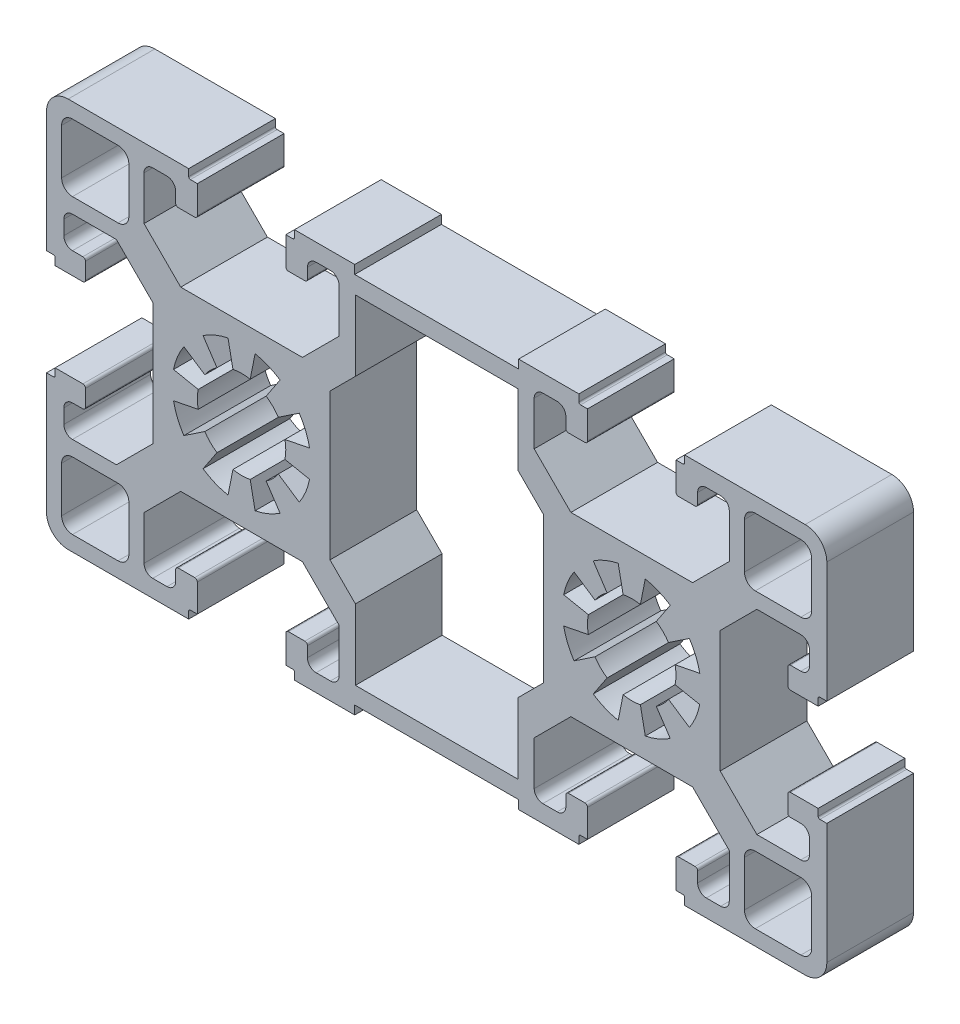
SolidWorks part; units mm, degrees
ref_plane "前视基准面" through (0, 0, 0) normal (0, 0, 1) x (1, 0, 0)
ref_plane "上视基准面" through (0, 0, 0) normal (0, 1, 0) x (1, 0, 0)
ref_plane "右视基准面" through (0, 0, 0) normal (1, 0, 0) x (0, 0, -1)
sketch "草图1" plane through (0, 0, 0) normal (0, 0, 1) x (1, 0, 0)
  line L0 (-64.3456, 3.0482) -> (-78.2456, 3.0482)
  line L1 (-80.7456, 0.5482) -> (-80.7456, -13.3518)
  line L2 (-63.3456, 2.0482) -> (-63.3456, -1.1518)
  line L3 (-63.6456, -1.4518) -> (-65.5456, -1.4518)
  line L4 (-65.8456, -1.1518) -> (-65.8456, 0.0482)
  line L5 (-66.8456, 1.0482) -> (-68.4956, 1.0482)
  line L6 (-69.4956, 0.0482) -> (-69.4956, -5.0198)
  line L7 (-77.7456, -6.4518) -> (-72.4956, -6.4518)
  line L8 (-71.2456, -5.2018) -> (-71.2456, 0.0482)
  line L9 (-72.4956, 1.2982) -> (-77.7456, 1.2982)
  line L10 (-78.9956, 0.0482) -> (-78.9956, -5.2018)
  line L11 (-72.6776, -8.2018) -> (-77.7456, -8.2018)
  line L12 (-78.7456, -9.2018) -> (-78.7456, -10.8518)
  line L13 (-77.7456, -11.8518) -> (-76.5456, -11.8518)
  line L14 (-76.2456, -12.1518) -> (-76.2456, -14.0518)
  line L15 (-76.5456, -14.3518) -> (-79.7456, -14.3518)
  line L16 (-63.3456, 2.0482) -> (-64.1456, 2.0482)
  line L17 (-64.3456, 2.2482) -> (-64.3456, 3.0482)
  line L18 (-80.7456, -13.3518) -> (-79.9456, -13.3518)
  line L19 (-79.7456, -13.5518) -> (-79.7456, -14.3518)
  line L20 (-53.1456, 2.0482) -> (-53.1456, -1.1518)
  line L21 (-52.8456, -1.4518) -> (-50.9456, -1.4518)
  line L22 (-50.6456, -1.1518) -> (-50.6456, 0.0482)
  line L23 (-49.6456, 1.0482) -> (-47.9956, 1.0482)
  line L24 (-46.9956, 0.0482) -> (-46.9956, -5.0198)
  line L25 (-53.1456, 2.0482) -> (-52.3456, 2.0482)
  line L26 (-52.1456, 2.2482) -> (-52.1456, 3.0482)
  line L27 (-64.3456, -41.9518) -> (-78.2456, -41.9518)
  line L28 (-80.7456, -39.4518) -> (-80.7456, -25.5518)
  line L29 (-63.3456, -40.9518) -> (-63.3456, -37.7518)
  line L30 (-63.6456, -37.4518) -> (-65.5456, -37.4518)
  line L31 (-65.8456, -37.7518) -> (-65.8456, -38.9518)
  line L32 (-66.8456, -39.9518) -> (-68.4956, -39.9518)
  line L33 (-69.4956, -38.9518) -> (-69.4956, -33.8838)
  line L34 (-77.7456, -32.4518) -> (-72.4956, -32.4518)
  line L35 (-71.2456, -33.7018) -> (-71.2456, -38.9518)
  line L36 (-72.4956, -40.2018) -> (-77.7456, -40.2018)
  line L37 (-78.9956, -38.9518) -> (-78.9956, -33.7018)
  line L38 (-72.6776, -30.7018) -> (-77.7456, -30.7018)
  line L39 (-78.7456, -29.7018) -> (-78.7456, -28.0518)
  line L40 (-77.7456, -27.0518) -> (-76.5456, -27.0518)
  line L41 (-76.2456, -26.7518) -> (-76.2456, -24.8518)
  line L42 (-76.5456, -24.5518) -> (-79.7456, -24.5518)
  line L43 (-63.3456, -40.9518) -> (-64.1456, -40.9518)
  line L44 (-64.3456, -41.1518) -> (-64.3456, -41.9518)
  line L45 (-80.7456, -25.5518) -> (-79.9456, -25.5518)
  line L46 (-79.7456, -25.3518) -> (-79.7456, -24.5518)
  line L47 (-53.1456, -40.9518) -> (-53.1456, -37.7518)
  line L48 (-52.8456, -37.4518) -> (-50.9456, -37.4518)
  line L49 (-50.6456, -37.7518) -> (-50.6456, -38.9518)
  line L50 (-49.6456, -39.9518) -> (-47.9956, -39.9518)
  line L51 (-46.9956, -38.9518) -> (-46.9956, -33.8838)
  line L52 (-53.1456, -40.9518) -> (-52.3456, -40.9518)
  line L53 (-52.1456, -41.1518) -> (-52.1456, -41.9518)
  line L54 (-62.6902, -26.1035) -> (-61.079, -23.6923)
  line L55 (-59.8063, -27.2981) -> (-59.2406, -24.4538)
  line L56 (-56.6849, -27.2981) -> (-57.2507, -24.4538)
  line L57 (-53.8011, -26.1035) -> (-55.4122, -23.6923)
  line L58 (-51.5939, -23.8964) -> (-54.0051, -22.2852)
  line L59 (-50.3993, -21.0125) -> (-53.2436, -20.4467)
  line L60 (-50.3993, -17.8911) -> (-53.2436, -18.4568)
  line L61 (-51.5939, -15.0072) -> (-54.0051, -16.6184)
  line L62 (-53.8011, -12.8) -> (-55.4122, -15.2113)
  line L63 (-56.6849, -11.6055) -> (-57.2507, -14.4498)
  line L64 (-59.8063, -11.6055) -> (-59.2406, -14.4498)
  line L65 (-62.6902, -12.8) -> (-61.079, -15.2113)
  line L66 (-64.8974, -15.0072) -> (-62.4861, -16.6184)
  line L67 (-66.0919, -17.8911) -> (-63.2476, -18.4568)
  line L68 (-66.0919, -21.0125) -> (-63.2476, -20.4467)
  line L69 (-64.8974, -23.8964) -> (-62.4861, -22.2852)
  line L71 (-51.2276, -9.2518) -> (-65.2636, -9.2518)
  line L72 (-68.4456, -12.4338) -> (-68.4456, -26.4698)
  line L73 (-65.2636, -29.6518) -> (-51.2276, -29.6518)
  line L74 (-69.4956, -5.0198) -> (-65.2636, -9.2518)
  line L75 (-72.6776, -8.2018) -> (-68.4456, -12.4338)
  line L76 (-46.9956, -5.0198) -> (-51.2276, -9.2518)
  line L77 (-69.4956, -33.8838) -> (-65.2636, -29.6518)
  line L78 (-72.6776, -30.7018) -> (-68.4456, -26.4698)
  line L79 (-46.9956, -33.8838) -> (-51.2276, -29.6518)
  line L80 (-18.3456, 2.0482) -> (-18.3456, -1.1518)
  line L81 (-18.6456, -1.4518) -> (-20.5456, -1.4518)
  line L82 (-20.8456, -1.1518) -> (-20.8456, 0.0482)
  line L83 (-21.8456, 1.0482) -> (-23.4956, 1.0482)
  line L84 (-24.4956, 0.0482) -> (-24.4956, -5.0198)
  line L85 (-18.3456, 2.0482) -> (-19.1456, 2.0482)
  line L86 (-19.3456, 2.2482) -> (-19.3456, 3.0482)
  line L87 (-7.1456, 3.0482) -> (6.7544, 3.0482)
  line L88 (9.2544, 0.5482) -> (9.2544, -13.3518)
  line L89 (-8.1456, 2.0482) -> (-8.1456, -1.1518)
  line L90 (-7.8456, -1.4518) -> (-5.9456, -1.4518)
  line L91 (-5.6456, -1.1518) -> (-5.6456, 0.0482)
  line L92 (-4.6456, 1.0482) -> (-2.9956, 1.0482)
  line L93 (-1.9956, 0.0482) -> (-1.9956, -5.0198)
  line L94 (6.2544, -6.4518) -> (1.0044, -6.4518)
  line L95 (-0.2456, -5.2018) -> (-0.2456, 0.0482)
  line L96 (1.0044, 1.2982) -> (6.2544, 1.2982)
  line L97 (7.5044, 0.0482) -> (7.5044, -5.2018)
  line L98 (1.1864, -8.2018) -> (6.2544, -8.2018)
  line L99 (7.2544, -9.2018) -> (7.2544, -10.8518)
  line L100 (6.2544, -11.8518) -> (5.0544, -11.8518)
  line L101 (4.7544, -12.1518) -> (4.7544, -14.0518)
  line L102 (5.0544, -14.3518) -> (8.2544, -14.3518)
  line L103 (-8.1456, 2.0482) -> (-7.3456, 2.0482)
  line L104 (-7.1456, 2.2482) -> (-7.1456, 3.0482)
  line L105 (9.2544, -13.3518) -> (8.4544, -13.3518)
  line L106 (8.2544, -13.5518) -> (8.2544, -14.3518)
  line L107 (-18.3456, -40.9518) -> (-18.3456, -37.7518)
  line L108 (-18.6456, -37.4518) -> (-20.5456, -37.4518)
  line L109 (-20.8456, -37.7518) -> (-20.8456, -38.9518)
  line L110 (-21.8456, -39.9518) -> (-23.4956, -39.9518)
  line L111 (-24.4956, -38.9518) -> (-24.4956, -33.8838)
  line L112 (-18.3456, -40.9518) -> (-19.1456, -40.9518)
  line L113 (-19.3456, -41.1518) -> (-19.3456, -41.9518)
  line L114 (-7.1456, -41.9518) -> (6.7544, -41.9518)
  line L115 (9.2544, -39.4518) -> (9.2544, -25.5518)
  line L116 (-8.1456, -40.9518) -> (-8.1456, -37.7518)
  line L117 (-7.8456, -37.4518) -> (-5.9456, -37.4518)
  line L118 (-5.6456, -37.7518) -> (-5.6456, -38.9518)
  line L119 (-4.6456, -39.9518) -> (-2.9956, -39.9518)
  line L120 (-1.9956, -38.9518) -> (-1.9956, -33.8838)
  line L121 (6.2544, -32.4518) -> (1.0044, -32.4518)
  line L122 (-0.2456, -33.7018) -> (-0.2456, -38.9518)
  line L123 (1.0044, -40.2018) -> (6.2544, -40.2018)
  line L124 (7.5044, -38.9518) -> (7.5044, -33.7018)
  line L125 (1.1864, -30.7018) -> (6.2544, -30.7018)
  line L126 (7.2544, -29.7018) -> (7.2544, -28.0518)
  line L127 (6.2544, -27.0518) -> (5.0544, -27.0518)
  line L128 (4.7544, -26.7518) -> (4.7544, -24.8518)
  line L129 (5.0544, -24.5518) -> (8.2544, -24.5518)
  line L130 (-8.1456, -40.9518) -> (-7.3456, -40.9518)
  line L131 (-7.1456, -41.1518) -> (-7.1456, -41.9518)
  line L132 (9.2544, -25.5518) -> (8.4544, -25.5518)
  line L133 (8.2544, -25.3518) -> (8.2544, -24.5518)
  line L134 (-17.6902, -26.1035) -> (-16.079, -23.6923)
  line L135 (-14.8063, -27.2981) -> (-14.2406, -24.4538)
  line L136 (-11.6849, -27.2981) -> (-12.2507, -24.4538)
  line L137 (-8.8011, -26.1035) -> (-10.4122, -23.6923)
  line L138 (-6.5939, -23.8964) -> (-9.0051, -22.2852)
  line L139 (-5.3993, -21.0125) -> (-8.2436, -20.4467)
  line L140 (-5.3993, -17.8911) -> (-8.2436, -18.4568)
  line L141 (-6.5939, -15.0072) -> (-9.0051, -16.6184)
  line L142 (-8.8011, -12.8) -> (-10.4122, -15.2113)
  line L143 (-11.6849, -11.6055) -> (-12.2507, -14.4498)
  line L144 (-14.8063, -11.6055) -> (-14.2406, -14.4498)
  line L145 (-17.6902, -12.8) -> (-16.079, -15.2113)
  line L146 (-19.8974, -15.0072) -> (-17.4861, -16.6184)
  line L147 (-21.0919, -17.8911) -> (-18.2476, -18.4568)
  line L148 (-21.0919, -21.0125) -> (-18.2476, -20.4467)
  line L149 (-19.8974, -23.8964) -> (-17.4861, -22.2852)
  line L150 (-3.0456, -26.4698) -> (-3.0456, -12.4338)
  line L151 (-6.2276, -9.2518) -> (-20.2636, -9.2518)
  line L153 (-20.2636, -29.6518) -> (-6.2276, -29.6518)
  line L154 (-24.4956, -5.0198) -> (-20.2636, -9.2518)
  line L155 (-1.9956, -5.0198) -> (-6.2276, -9.2518)
  line L156 (1.1864, -8.2018) -> (-3.0456, -12.4338)
  line L157 (-24.4956, -33.8838) -> (-20.2636, -29.6518)
  line L158 (-1.9956, -33.8838) -> (-6.2276, -29.6518)
  line L159 (1.1864, -30.7018) -> (-3.0456, -26.4698)
  line L160 (-52.1456, 3.0482) -> (-45.1956, 3.0482)
  line L161 (-45.1956, 2.0482) -> (-26.2956, 2.0482)
  line L162 (-45.1163, 0.0482) -> (-26.375, 0.0482)
  line L163 (-45.1163, -8.0902) -> (-48.0456, -11.0196)
  line L164 (-45.1163, -30.8134) -> (-48.0456, -27.884)
  line L165 (-19.3456, 3.0482) -> (-26.2956, 3.0482)
  line L166 (-26.375, -8.0902) -> (-23.4456, -11.0196)
  line L167 (-26.375, -30.8134) -> (-23.4456, -27.884)
  line L168 (-52.1456, -41.9518) -> (-45.1956, -41.9518)
  line L169 (-26.2956, -41.9518) -> (-19.3456, -41.9518)
  line L170 (-45.1956, -40.9518) -> (-26.2956, -40.9518)
  line L171 (-26.2956, -41.9518) -> (-26.2956, -40.9518)
  line L172 (-26.2956, 2.0482) -> (-26.2956, 3.0482)
  line L173 (-45.1956, -41.9518) -> (-45.1956, -40.9518)
  line L174 (-45.1956, 2.0482) -> (-45.1956, 3.0482)
  line L175 (-48.0456, -11.0196) -> (-48.0456, -27.884)
  line L176 (-23.4456, -11.0196) -> (-23.4456, -27.884)
  line L177 (-45.1163, -8.0902) -> (-45.1163, 0.0482)
  line L178 (-26.375, -8.0902) -> (-26.375, 0.0482)
  line L179 (-45.1163, -38.9518) -> (-26.375, -38.9518)
  line L180 (-45.1163, -30.8134) -> (-45.1163, -38.9518)
  line L181 (-26.375, -30.8134) -> (-26.375, -38.9518)
  arc A0 (-78.2456, 3.0482) -> (-80.7456, 0.5482) centre (-78.2456, 0.5482) ccw
  arc A1 (-63.6456, -1.4518) -> (-63.3456, -1.1518) centre (-63.6456, -1.1518) ccw
  arc A2 (-65.8456, -1.1518) -> (-65.5456, -1.4518) centre (-65.5456, -1.1518) ccw
  arc A3 (-65.8456, 0.0482) -> (-66.8456, 1.0482) centre (-66.8456, 0.0482) ccw
  arc A4 (-68.4956, 1.0482) -> (-69.4956, 0.0482) centre (-68.4956, 0.0482) ccw
  arc A5 (-72.4956, -6.4518) -> (-71.2456, -5.2018) centre (-72.4956, -5.2018) ccw
  arc A6 (-71.2456, 0.0482) -> (-72.4956, 1.2982) centre (-72.4956, 0.0482) ccw
  arc A7 (-77.7456, 1.2982) -> (-78.9956, 0.0482) centre (-77.7456, 0.0482) ccw
  arc A8 (-78.9956, -5.2018) -> (-77.7456, -6.4518) centre (-77.7456, -5.2018) ccw
  arc A9 (-77.7456, -8.2018) -> (-78.7456, -9.2018) centre (-77.7456, -9.2018) ccw
  arc A10 (-78.7456, -10.8518) -> (-77.7456, -11.8518) centre (-77.7456, -10.8518) ccw
  arc A11 (-76.2456, -12.1518) -> (-76.5456, -11.8518) centre (-76.5456, -12.1518) ccw
  arc A12 (-76.5456, -14.3518) -> (-76.2456, -14.0518) centre (-76.5456, -14.0518) ccw
  arc A13 (-64.3456, 2.2482) -> (-64.1456, 2.0482) centre (-64.1456, 2.2482) ccw
  arc A14 (-79.7456, -13.5518) -> (-79.9456, -13.3518) centre (-79.9456, -13.5518) ccw
  arc A15 (-59.2406, -24.4538) -> (-57.2507, -24.4538) centre (-58.2456, -19.4518) ccw
  arc A16 (-55.4122, -23.6923) -> (-54.0051, -22.2852) centre (-58.2456, -19.4518) ccw
  arc A17 (-53.2436, -20.4467) -> (-53.2436, -18.4568) centre (-58.2456, -19.4518) ccw
  arc A18 (-54.0051, -16.6184) -> (-55.4122, -15.2113) centre (-58.2456, -19.4518) ccw
  arc A19 (-57.2507, -14.4498) -> (-59.2406, -14.4498) centre (-58.2456, -19.4518) ccw
  arc A20 (-61.079, -15.2113) -> (-62.4861, -16.6184) centre (-58.2456, -19.4518) ccw
  arc A21 (-63.2476, -18.4568) -> (-63.2476, -20.4467) centre (-58.2456, -19.4518) ccw
  arc A22 (-62.4861, -22.2852) -> (-61.079, -23.6923) centre (-58.2456, -19.4518) ccw
  arc A23 (-62.6902, -26.1035) -> (-59.8063, -27.2981) centre (-58.2456, -19.4518) ccw
  arc A24 (-56.6849, -27.2981) -> (-53.8011, -26.1035) centre (-58.2456, -19.4518) ccw
  arc A25 (-51.5939, -23.8964) -> (-50.3993, -21.0125) centre (-58.2456, -19.4518) ccw
  arc A26 (-50.3993, -17.8911) -> (-51.5939, -15.0072) centre (-58.2456, -19.4518) ccw
  arc A27 (-53.8011, -12.8) -> (-56.6849, -11.6055) centre (-58.2456, -19.4518) ccw
  arc A28 (-59.8063, -11.6055) -> (-62.6902, -12.8) centre (-58.2456, -19.4518) ccw
  arc A29 (-64.8974, -15.0072) -> (-66.0919, -17.8911) centre (-58.2456, -19.4518) ccw
  arc A30 (-66.0919, -21.0125) -> (-64.8974, -23.8964) centre (-58.2456, -19.4518) ccw
  arc A31 (-53.1456, -1.1518) -> (-52.8456, -1.4518) centre (-52.8456, -1.1518) ccw
  arc A32 (-50.9456, -1.4518) -> (-50.6456, -1.1518) centre (-50.9456, -1.1518) ccw
  arc A33 (-49.6456, 1.0482) -> (-50.6456, 0.0482) centre (-49.6456, 0.0482) ccw
  arc A34 (-46.9956, 0.0482) -> (-47.9956, 1.0482) centre (-47.9956, 0.0482) ccw
  arc A35 (-52.3456, 2.0482) -> (-52.1456, 2.2482) centre (-52.3456, 2.2482) ccw
  arc A36 (-80.7456, -39.4518) -> (-78.2456, -41.9518) centre (-78.2456, -39.4518) ccw
  arc A37 (-63.3456, -37.7518) -> (-63.6456, -37.4518) centre (-63.6456, -37.7518) ccw
  arc A38 (-65.5456, -37.4518) -> (-65.8456, -37.7518) centre (-65.5456, -37.7518) ccw
  arc A39 (-66.8456, -39.9518) -> (-65.8456, -38.9518) centre (-66.8456, -38.9518) ccw
  arc A40 (-69.4956, -38.9518) -> (-68.4956, -39.9518) centre (-68.4956, -38.9518) ccw
  arc A41 (-71.2456, -33.7018) -> (-72.4956, -32.4518) centre (-72.4956, -33.7018) ccw
  arc A42 (-72.4956, -40.2018) -> (-71.2456, -38.9518) centre (-72.4956, -38.9518) ccw
  arc A43 (-78.9956, -38.9518) -> (-77.7456, -40.2018) centre (-77.7456, -38.9518) ccw
  arc A44 (-77.7456, -32.4518) -> (-78.9956, -33.7018) centre (-77.7456, -33.7018) ccw
  arc A45 (-78.7456, -29.7018) -> (-77.7456, -30.7018) centre (-77.7456, -29.7018) ccw
  arc A46 (-77.7456, -27.0518) -> (-78.7456, -28.0518) centre (-77.7456, -28.0518) ccw
  arc A47 (-76.5456, -27.0518) -> (-76.2456, -26.7518) centre (-76.5456, -26.7518) ccw
  arc A48 (-76.2456, -24.8518) -> (-76.5456, -24.5518) centre (-76.5456, -24.8518) ccw
  arc A49 (-64.1456, -40.9518) -> (-64.3456, -41.1518) centre (-64.1456, -41.1518) ccw
  arc A50 (-79.9456, -25.5518) -> (-79.7456, -25.3518) centre (-79.9456, -25.3518) ccw
  arc A51 (-52.8456, -37.4518) -> (-53.1456, -37.7518) centre (-52.8456, -37.7518) ccw
  arc A52 (-50.6456, -37.7518) -> (-50.9456, -37.4518) centre (-50.9456, -37.7518) ccw
  arc A53 (-50.6456, -38.9518) -> (-49.6456, -39.9518) centre (-49.6456, -38.9518) ccw
  arc A54 (-47.9956, -39.9518) -> (-46.9956, -38.9518) centre (-47.9956, -38.9518) ccw
  arc A55 (-52.1456, -41.1518) -> (-52.3456, -40.9518) centre (-52.3456, -41.1518) ccw
  arc A56 (-18.6456, -1.4518) -> (-18.3456, -1.1518) centre (-18.6456, -1.1518) ccw
  arc A57 (-20.8456, -1.1518) -> (-20.5456, -1.4518) centre (-20.5456, -1.1518) ccw
  arc A58 (-20.8456, 0.0482) -> (-21.8456, 1.0482) centre (-21.8456, 0.0482) ccw
  arc A59 (-23.4956, 1.0482) -> (-24.4956, 0.0482) centre (-23.4956, 0.0482) ccw
  arc A60 (-19.3456, 2.2482) -> (-19.1456, 2.0482) centre (-19.1456, 2.2482) ccw
  arc A61 (-14.2406, -24.4538) -> (-12.2507, -24.4538) centre (-13.2456, -19.4518) ccw
  arc A62 (-10.4122, -23.6923) -> (-9.0051, -22.2852) centre (-13.2456, -19.4518) ccw
  arc A63 (-8.2436, -20.4467) -> (-8.2436, -18.4568) centre (-13.2456, -19.4518) ccw
  arc A64 (-9.0051, -16.6184) -> (-10.4122, -15.2113) centre (-13.2456, -19.4518) ccw
  arc A65 (-12.2507, -14.4498) -> (-14.2406, -14.4498) centre (-13.2456, -19.4518) ccw
  arc A66 (-16.079, -15.2113) -> (-17.4861, -16.6184) centre (-13.2456, -19.4518) ccw
  arc A67 (-18.2476, -18.4568) -> (-18.2476, -20.4467) centre (-13.2456, -19.4518) ccw
  arc A68 (-17.4861, -22.2852) -> (-16.079, -23.6923) centre (-13.2456, -19.4518) ccw
  arc A69 (-17.6902, -26.1035) -> (-14.8063, -27.2981) centre (-13.2456, -19.4518) ccw
  arc A70 (-11.6849, -27.2981) -> (-8.8011, -26.1035) centre (-13.2456, -19.4518) ccw
  arc A71 (-6.5939, -23.8964) -> (-5.3993, -21.0125) centre (-13.2456, -19.4518) ccw
  arc A72 (-5.3993, -17.8911) -> (-6.5939, -15.0072) centre (-13.2456, -19.4518) ccw
  arc A73 (-8.8011, -12.8) -> (-11.6849, -11.6055) centre (-13.2456, -19.4518) ccw
  arc A74 (-14.8063, -11.6055) -> (-17.6902, -12.8) centre (-13.2456, -19.4518) ccw
  arc A75 (-19.8974, -15.0072) -> (-21.0919, -17.8911) centre (-13.2456, -19.4518) ccw
  arc A76 (-21.0919, -21.0125) -> (-19.8974, -23.8964) centre (-13.2456, -19.4518) ccw
  arc A77 (9.2544, 0.5482) -> (6.7544, 3.0482) centre (6.7544, 0.5482) ccw
  arc A78 (-8.1456, -1.1518) -> (-7.8456, -1.4518) centre (-7.8456, -1.1518) ccw
  arc A79 (-5.9456, -1.4518) -> (-5.6456, -1.1518) centre (-5.9456, -1.1518) ccw
  arc A80 (-4.6456, 1.0482) -> (-5.6456, 0.0482) centre (-4.6456, 0.0482) ccw
  arc A81 (-1.9956, 0.0482) -> (-2.9956, 1.0482) centre (-2.9956, 0.0482) ccw
  arc A82 (-0.2456, -5.2018) -> (1.0044, -6.4518) centre (1.0044, -5.2018) ccw
  arc A83 (1.0044, 1.2982) -> (-0.2456, 0.0482) centre (1.0044, 0.0482) ccw
  arc A84 (7.5044, 0.0482) -> (6.2544, 1.2982) centre (6.2544, 0.0482) ccw
  arc A85 (6.2544, -6.4518) -> (7.5044, -5.2018) centre (6.2544, -5.2018) ccw
  arc A86 (7.2544, -9.2018) -> (6.2544, -8.2018) centre (6.2544, -9.2018) ccw
  arc A87 (6.2544, -11.8518) -> (7.2544, -10.8518) centre (6.2544, -10.8518) ccw
  arc A88 (5.0544, -11.8518) -> (4.7544, -12.1518) centre (5.0544, -12.1518) ccw
  arc A89 (4.7544, -14.0518) -> (5.0544, -14.3518) centre (5.0544, -14.0518) ccw
  arc A90 (-7.3456, 2.0482) -> (-7.1456, 2.2482) centre (-7.3456, 2.2482) ccw
  arc A91 (8.4544, -13.3518) -> (8.2544, -13.5518) centre (8.4544, -13.5518) ccw
  arc A92 (-18.3456, -37.7518) -> (-18.6456, -37.4518) centre (-18.6456, -37.7518) ccw
  arc A93 (-20.5456, -37.4518) -> (-20.8456, -37.7518) centre (-20.5456, -37.7518) ccw
  arc A94 (-21.8456, -39.9518) -> (-20.8456, -38.9518) centre (-21.8456, -38.9518) ccw
  arc A95 (-24.4956, -38.9518) -> (-23.4956, -39.9518) centre (-23.4956, -38.9518) ccw
  arc A96 (-19.1456, -40.9518) -> (-19.3456, -41.1518) centre (-19.1456, -41.1518) ccw
  arc A97 (6.7544, -41.9518) -> (9.2544, -39.4518) centre (6.7544, -39.4518) ccw
  arc A98 (-7.8456, -37.4518) -> (-8.1456, -37.7518) centre (-7.8456, -37.7518) ccw
  arc A99 (-5.6456, -37.7518) -> (-5.9456, -37.4518) centre (-5.9456, -37.7518) ccw
  arc A100 (-5.6456, -38.9518) -> (-4.6456, -39.9518) centre (-4.6456, -38.9518) ccw
  arc A101 (-2.9956, -39.9518) -> (-1.9956, -38.9518) centre (-2.9956, -38.9518) ccw
  arc A102 (1.0044, -32.4518) -> (-0.2456, -33.7018) centre (1.0044, -33.7018) ccw
  arc A103 (-0.2456, -38.9518) -> (1.0044, -40.2018) centre (1.0044, -38.9518) ccw
  arc A104 (6.2544, -40.2018) -> (7.5044, -38.9518) centre (6.2544, -38.9518) ccw
  arc A105 (7.5044, -33.7018) -> (6.2544, -32.4518) centre (6.2544, -33.7018) ccw
  arc A106 (6.2544, -30.7018) -> (7.2544, -29.7018) centre (6.2544, -29.7018) ccw
  arc A107 (7.2544, -28.0518) -> (6.2544, -27.0518) centre (6.2544, -28.0518) ccw
  arc A108 (4.7544, -26.7518) -> (5.0544, -27.0518) centre (5.0544, -26.7518) ccw
  arc A109 (5.0544, -24.5518) -> (4.7544, -24.8518) centre (5.0544, -24.8518) ccw
  arc A110 (-7.1456, -41.1518) -> (-7.3456, -40.9518) centre (-7.3456, -41.1518) ccw
  arc A111 (8.2544, -25.3518) -> (8.4544, -25.5518) centre (8.4544, -25.3518) ccw
extrude "凸台-拉伸1" add sketch "草图1" along normal blind 10
